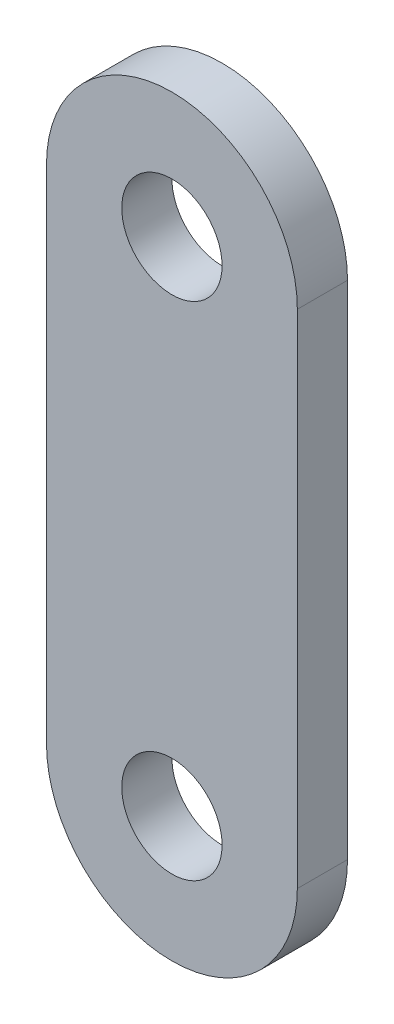
SolidWorks part; units mm, degrees
ref_plane "Alzado" through (0, 0, 0) normal (0, 0, 1) x (1, 0, 0)
ref_plane "Planta" through (0, 0, 0) normal (0, 1, 0) x (1, 0, 0)
ref_plane "Vista lateral" through (0, 0, 0) normal (1, 0, 0) x (0, 0, -1)
sketch "Croquis1" plane through (0, 0, 0) normal (0, 0, 1) x (1, 0, 0)
  line L0 (0, 0) -> (50, 0) construction
  line L1 (50, 0) -> (50, 100)
  line L2 (50, 100) -> (0, 100) construction
  line L3 (0, 100) -> (0, 0)
  arc A0 (0, 0) -> (50, 0) centre (25, 0) ccw
  arc A1 (50, 100) -> (0, 100) centre (25, 100) ccw
  circle A2 centre (25, 100) radius 10
  circle A3 centre (25, 0) radius 10
  dimension "D3" = 20
  dimension "D4" = 20
  dimension "D1" = 50
  dimension "D2" = 100
extrude "Saliente-Extruir1" add sketch "Croquis1" along normal blind 10
